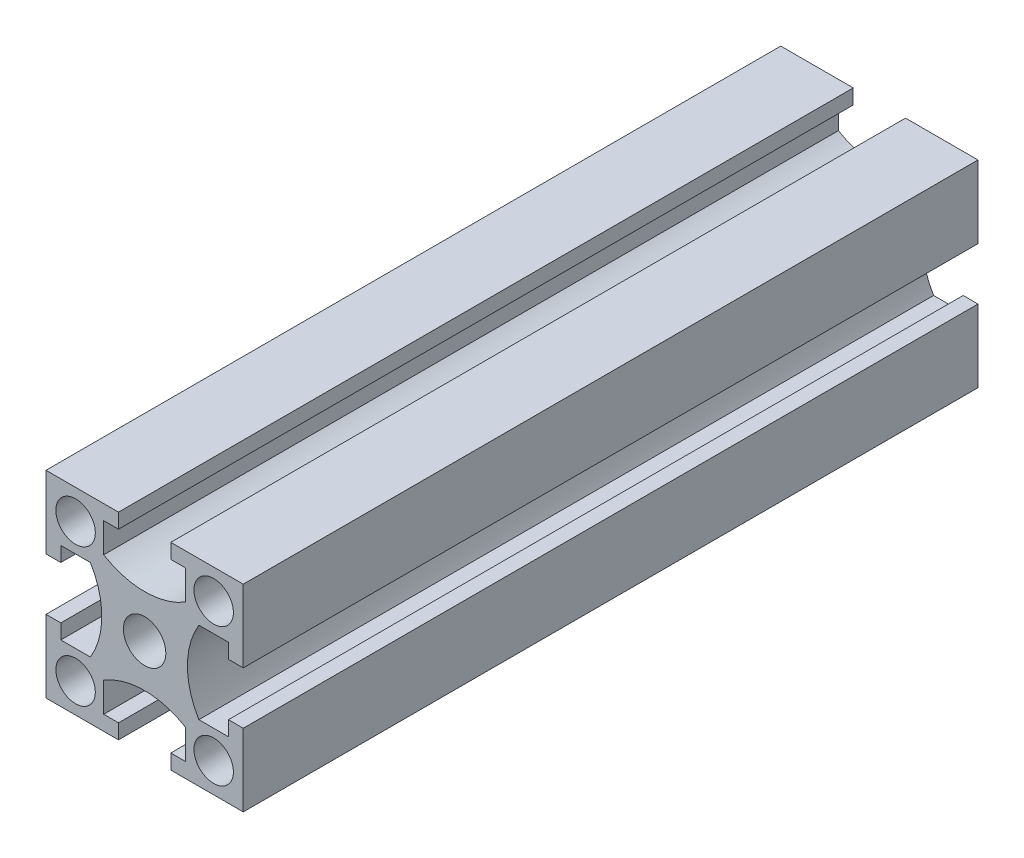
SolidWorks part; units mm, degrees
material "6061-T6 (SS)"
ref_plane "정면" through (0, 0, 0) normal (0, 0, 1) x (1, 0, 0)
ref_plane "윗면" through (0, 0, 0) normal (0, 1, 0) x (1, 0, 0)
ref_plane "우측면" through (0, 0, 0) normal (1, 0, 0) x (0, 0, -1)
sketch "스케치1" plane through (0, 0, 0) normal (0, 0, 1) x (1, 0, 0)
  line L1 (-10, 10) -> (10, 10)
  line L2 (-10, 10) -> (-10, -10)
  line L3 (-10, -10) -> (10, -10)
  line L4 (10, 10) -> (10, -10)
  line L5 (-10, 10) -> (10, -10) construction
  line L6 (-10, -10) -> (10, 10) construction
  point P0 (0, 0)
  dimension "D1" = 20
  dimension "D2" = 20
extrude "보스-돌출1" add sketch "스케치1" along normal blind 74.5
sketch "스케치2" plane through (0, 0, 74.5) normal (0, 0, 1) x (1, 0, 0)
  line L0 (-2.65, 10) -> (-2.65, 8.5)
  line L1 (10, 10) -> (-10, 10) construction
  line L2 (-2.65, 8.5) -> (-4.15, 8.5)
  line L3 (-4.15, 8.5) -> (-4.15, 5.5)
  line L4 (-2.65, 10) -> (2.65, 10)
  line L5 (2.65, 10) -> (2.65, 8.5)
  line L6 (2.65, 8.5) -> (4.15, 8.5)
  line L7 (4.15, 8.5) -> (4.15, 5.5)
  line L8 (10, 2.65) -> (8.5, 2.65)
  line L9 (8.5, 2.65) -> (8.5, 4.15)
  line L10 (8.5, 4.15) -> (5.5, 4.15)
  line L11 (10, 2.65) -> (10, -2.65)
  line L12 (10, -2.65) -> (8.5, -2.65)
  line L13 (8.5, -2.65) -> (8.5, -4.15)
  line L14 (8.5, -4.15) -> (5.5, -4.15)
  line L15 (2.65, -10) -> (2.65, -8.5)
  line L16 (2.65, -8.5) -> (4.15, -8.5)
  line L17 (4.15, -8.5) -> (4.15, -5.5)
  line L18 (2.65, -10) -> (-2.65, -10)
  line L19 (-2.65, -10) -> (-2.65, -8.5)
  line L20 (-2.65, -8.5) -> (-4.15, -8.5)
  line L21 (-4.15, -8.5) -> (-4.15, -5.5)
  line L22 (-10, -2.65) -> (-8.5, -2.65)
  line L23 (-8.5, -2.65) -> (-8.5, -4.15)
  line L24 (-8.5, -4.15) -> (-5.5, -4.15)
  line L25 (-10, -2.65) -> (-10, 2.65)
  line L26 (-10, 2.65) -> (-8.5, 2.65)
  line L27 (-8.5, 2.65) -> (-8.5, 4.15)
  line L28 (-8.5, 4.15) -> (-5.5, 4.15)
  arc A1 (-4.15, 5.5) -> (4.15, 5.5) centre (0, 12.3394) ccw
  arc A2 (5.5, 4.15) -> (5.5, -4.15) centre (12.3394, 0) ccw
  arc A3 (4.15, -5.5) -> (-4.15, -5.5) centre (0, -12.3394) ccw
  arc A4 (-5.5, -4.15) -> (-5.5, 4.15) centre (-12.3394, 0) ccw
  circle A5 centre (0, 0) radius 2.15
  circle A6 centre (-7, 7) radius 2
  circle A7 centre (7, 7) radius 2
  circle A8 centre (7, -7) radius 2
  circle A9 centre (-7, -7) radius 2
  point P4 (-2.65, 9.25)
  point P43 (0, 0)
  dimension "D2" = 1.5
  dimension "D8" = 4.3
  dimension "D9" = 4
  dimension "D10" = 4
  dimension "D11" = 4
  dimension "D12" = 4
  dimension "D21" = 8
  dimension "D1" = 5.3
  dimension "D3" = 8.3
  dimension "D4" = 4.15
  dimension "D5" = 2.65
  dimension "D6" = 4
  dimension "D7" = 3
  dimension "D13" = 14
  dimension "D14" = 7
  dimension "D15" = 7
  dimension "D16" = 7
  dimension "D17" = 14
  dimension "D18" = 7
  dimension "D19" = 7
  dimension "D20" = 7
extrude "컷-돌출1" cut sketch "스케치2" against normal blind 315.5
